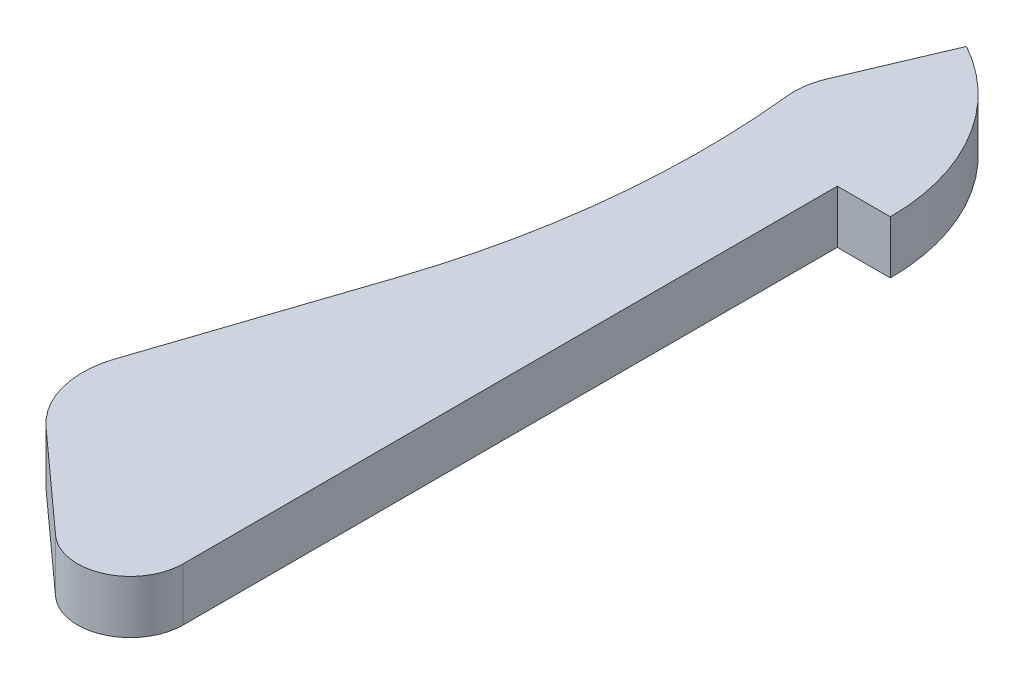
SolidWorks part; units mm, degrees
material "Pine"
ref_plane "Front Plane" through (0, 0, 0) normal (0, 0, 1) x (1, 0, 0)
ref_plane "Top Plane" through (0, 0, 0) normal (0, 1, 0) x (1, 0, 0)
ref_plane "Right Plane" through (0, 0, 0) normal (1, 0, 0) x (0, 0, -1)
sketch "Sketch1" plane through (0, 0, 0) normal (0, 1, 0) x (1, 0, 0)
  line L12 (0, 0) -> (0, -234.95)
  line L19 (0, -234.95) -> (-31.75, -249.0611) construction
  line L20 (-31.75, -249.0611) -> (-67.1399, -217.1119)
  line L21 (-75.9849, -183.5046) -> (-50.8, -107.95)
  line L22 (-37.0485, 18.9889) -> (-39.0627, 37.9321) construction
  line L23 (-37.0485, 18.9889) -> (-56.0985, 18.9889) construction
  line L24 (0, 0) -> (19.05, 0)
  line L25 (-20.2598, 66.675) -> (-35.1662, 31.6121)
  line L28 (19.05, 0) -> (19.05, -19.05) construction
  arc A8 (0, -234.95) -> (-31.75, -249.0611) centre (-19.0108, -234.95) cw
  arc A12 (-50.8, -107.95) -> (-37.0485, 18.9889) centre (-336.1943, -12.8186) ccw
  arc A13 (-67.1399, -217.1119) -> (-75.9849, -183.5046) centre (-45.8642, -193.5448) cw
  arc A14 (19.05, 0) -> (-20.2598, 66.675) centre (-57.15, 0) ccw
  arc A18 (-35.1662, 31.6121) -> (-37.0485, 18.9889) centre (-11.7909, 21.6745) ccw
  point P15 (-82.55, -203.2)
  dimension "D5" = 82.55
  dimension "D2" = 25.4
  dimension "D11" = 38.1
  dimension "D12" = 18.9889
  dimension "D8" = 31.75
  dimension "D9" = 19.05
  dimension "D13" = 76.2
  dimension "D1" = 234.95
  dimension "D3" = 107.95
  dimension "D4" = 203.2
  dimension "D6" = 50.8
  dimension "D7" = 31.75
  dimension "D10" = 66.675
extrude "Boss-Extrude1" add sketch "Sketch1" along normal blind 19.05
ref_plane "Plane1" through (0, 0, 253.9608) normal (0, 0, 1) x (1, 0, 0)
hole_wizard "1/8 (0.125) Diameter Hole1" positions "Sketch2" profile "Sketch3" hole size "1/8" standard "ANSI Inch"
sketch "Sketch2" plane through (0, 0, 0) normal (0, -1, 0) x (-1, 0, 0)
  line L0 (37.1909, 21.6745) -> (-15.9024, 21.6745) construction
  line L2 (59.2667, -133.35) -> (0, -133.35) construction
  line L3 (50.8, -107.95) -> (75.9849, -183.5046) construction
  line L4 (0, -234.95) -> (0, 0) construction
  line L6 (11.2898, -252.3223) -> (11.2898, -234.95) construction
  line L7 (11.2898, -234.95) -> (19.0108, -234.95) construction
  line L8 (19.0108, -234.95) -> (11.2898, -252.3223) construction
  line L12 (19.0108, -234.95) -> (22.2345, -227.6966) construction
  line L13 (0, 0) -> (-19.05, 0) construction
  arc A0 (37.0485, 18.9889) -> (35.1662, 31.6121) centre (11.7909, 21.6745) ccw construction
  arc A1 (20.2598, 66.675) -> (-19.05, 0) centre (57.15, 0) ccw construction
  arc A2 (0, -234.95) -> (31.75, -249.0611) centre (19.0108, -234.95) ccw construction
  point P2 (10.6442, 21.6745)
  point P4 (29.6333, -133.35)
  point P49 (22.2345, -227.6966)
  dimension "D1" = 7.9375
  dimension "D2" = 133.35
sketch "Sketch3" plane through (-10.6442, 0, -21.6745) normal (1, 0, 0) x (0, 0, -1)
  line L0 (0, 0) -> (0, 12.0791)
  line L1 (0, 12.0791) -> (1.5875, 11.1252)
  line L2 (1.5875, 11.1252) -> (1.5875, 0)
  line L5 (1.5875, 0) -> (0, 0)
  line L10 (0, 12.0791) -> (-1.5875, 11.1252) construction
  line L11 (0, -6.35) -> (0, 107.95) construction
  dimension "Hole Dia." = 3.175
  dimension "Hole Depth" = 11.1252
  dimension "Drill Angle" = 118
